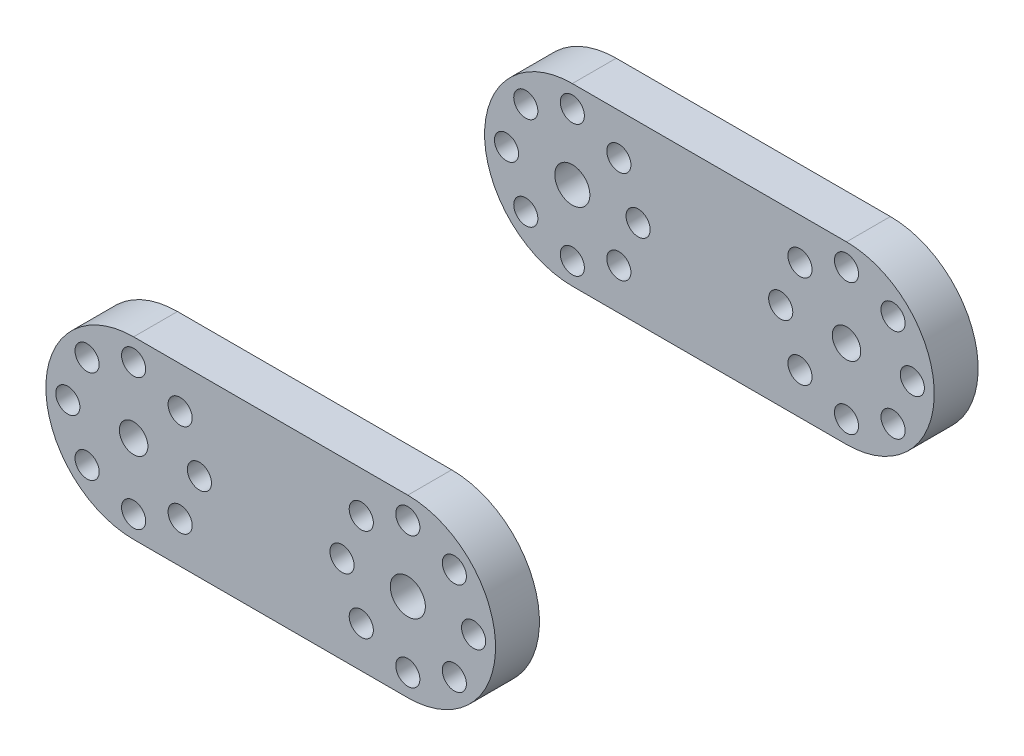
SolidWorks part; units mm, degrees
material "ABS"
ref_plane "正面" through (0, 0, 0) normal (0, 0, 1) x (1, 0, 0)
ref_plane "平面" through (0, 0, 0) normal (0, 1, 0) x (1, 0, 0)
ref_plane "右側面" through (0, 0, 0) normal (1, 0, 0) x (0, 0, -1)
sketch "ｽｹｯﾁ1" plane through (0, 0, 0) normal (0, 0, 1) x (1, 0, 0)
  line L0 (0, 8) -> (25, 8)
  line L1 (0, -8) -> (25, -8)
  arc A0 (0, 8) -> (0, -8) centre (0, 0) ccw
  arc A1 (25, -8) -> (25, 8) centre (25, 0) ccw
  circle A2 centre (0, 0) radius 1.3
  circle A3 centre (25, 0) radius 1.6
  circle A4 centre (0, 0) radius 6 construction
  circle A5 centre (25, 0) radius 6 construction
  circle A6 centre (0, 6) radius 1.1
  circle A7 centre (4.2426, 4.2426) radius 1.1
  circle A8 centre (6, 0) radius 1.1
  circle A9 centre (4.2426, -4.2426) radius 1.1
  circle A10 centre (0, -6) radius 1.1
  circle A11 centre (-4.2426, -4.2426) radius 1.1
  circle A12 centre (-6, 0) radius 1.1
  circle A13 centre (-4.2426, 4.2426) radius 1.1
  circle A14 centre (25, 6) radius 1.1
  circle A15 centre (29.2426, 4.2426) radius 1.1
  circle A16 centre (31, 0) radius 1.1
  circle A17 centre (29.2426, -4.2426) radius 1.1
  circle A18 centre (25, -6) radius 1.1
  circle A19 centre (20.7574, -4.2426) radius 1.1
  circle A20 centre (19, 0) radius 1.1
  circle A21 centre (20.7574, 4.2426) radius 1.1
  point P14 (33.2669, 13.5847)
  point P15 (0, 0)
  point P29 (0, 0)
  point P47 (25, 0)
  dimension "D1" = 8
  dimension "D2" = 2.6
  dimension "D3" = 3.2
  dimension "D4" = 12
  dimension "D5" = 25
  dimension "D6" = 8
  dimension "D7" = 2.2
  dimension "D8" = 2.2
  dimension "D9" = 8
extrude "ﾎﾞｽ - 押し出し1" add sketch "ｽｹｯﾁ1" along normal blind 4
ref_plane "平面1" through (0, 0, -36) normal (0, 0, -1) x (-1, 0, 0)
sketch "ｽｹｯﾁ3" plane through (0, 0, -36) normal (0, 0, -1) x (-1, 0, 0)
  line L2 (0, 8) -> (-25, 8)
  line L3 (-25, -8) -> (0, -8)
  line L4 (0, 8) -> (-25, 8)
  line L5 (-25, -8) -> (0, -8)
  circle A0 centre (-25, 0) radius 1.3
  circle A1 centre (0, 0) radius 1.6
  arc A2 (0, -8) -> (0, 8) centre (0, 0) ccw
  arc A3 (-25, 8) -> (-25, -8) centre (-25, 0) ccw
  arc A4 (0, -8) -> (0, 8) centre (0, 0) ccw
  arc A5 (-25, 8) -> (-25, -8) centre (-25, 0) ccw
  circle A6 centre (-31, 0) radius 1.1 construction
  circle A7 centre (-29.2426, 4.2426) radius 1.1 construction
  circle A8 centre (-25, 6) radius 1.1 construction
  circle A9 centre (-31, 0) radius 1.1
  circle A10 centre (-29.2426, 4.2426) radius 1.1
  circle A11 centre (-25, 6) radius 1.1
  circle A12 centre (-29.2426, -4.2426) radius 1.1 construction
  circle A13 centre (-29.2426, -4.2426) radius 1.1
  circle A14 centre (4.2426, -4.2426) radius 1.1 construction
  circle A15 centre (6, 0) radius 1.1 construction
  circle A16 centre (4.2426, 4.2426) radius 1.1 construction
  circle A17 centre (0, 6) radius 1.1 construction
  circle A18 centre (-4.2426, 4.2426) radius 1.1 construction
  circle A19 centre (-6, 0) radius 1.1 construction
  circle A20 centre (-4.2426, -4.2426) radius 1.1 construction
  circle A21 centre (0, -6) radius 1.1 construction
  circle A22 centre (-25, -6) radius 1.1 construction
  circle A23 centre (-20.7574, -4.2426) radius 1.1 construction
  circle A24 centre (-19, 0) radius 1.1 construction
  circle A25 centre (-20.7574, 4.2426) radius 1.1 construction
  circle A26 centre (4.2426, -4.2426) radius 1.1
  circle A27 centre (6, 0) radius 1.1
  circle A28 centre (4.2426, 4.2426) radius 1.1
  circle A29 centre (0, 6) radius 1.1
  circle A30 centre (-4.2426, 4.2426) radius 1.1
  circle A31 centre (-6, 0) radius 1.1
  circle A32 centre (-4.2426, -4.2426) radius 1.1
  circle A33 centre (0, -6) radius 1.1
  circle A34 centre (-25, -6) radius 1.1
  circle A35 centre (-20.7574, -4.2426) radius 1.1
  circle A36 centre (-19, 0) radius 1.1
  circle A37 centre (-20.7574, 4.2426) radius 1.1
  dimension "D2" = 3.2
  dimension "D3" = 2.6
  dimension "D1" = 0
extrude "ﾎﾞｽ - 押し出し2" add sketch "ｽｹｯﾁ3" along normal blind 4 separate body
ref_plane "平面2" through (0, 0, -18) normal (0, 0, 1) x (1, 0, 0)
